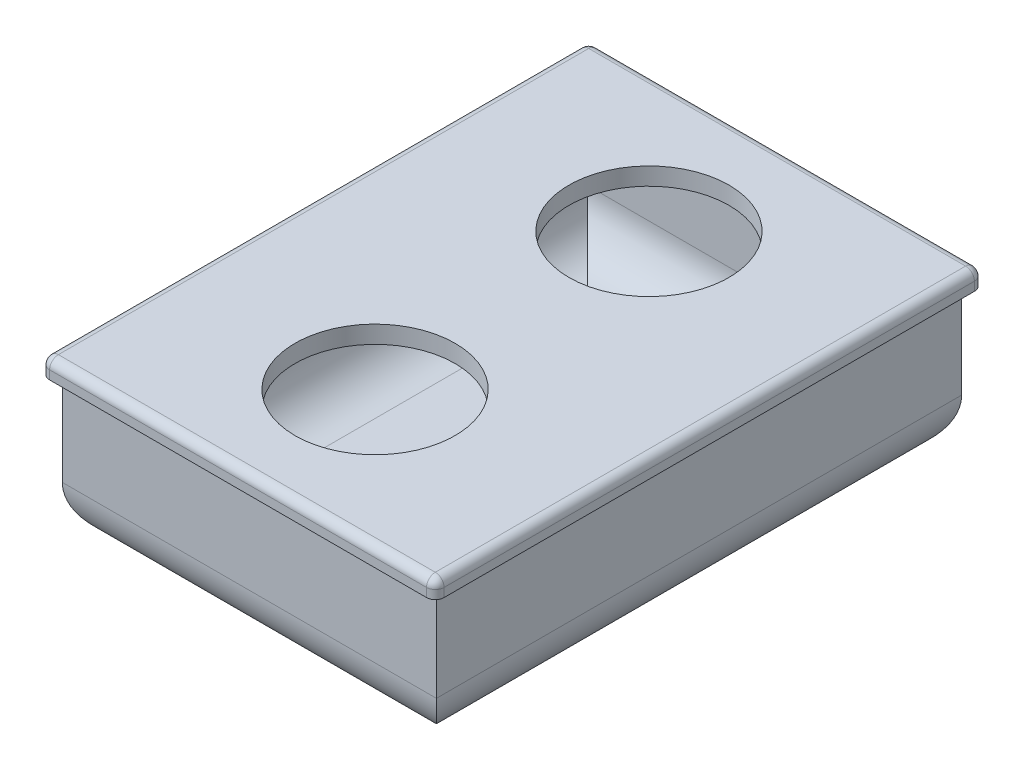
SolidWorks part; units mm, degrees
ref_plane "Front Plane" through (0, 0, 0) normal (0, 0, 1) x (1, 0, 0)
ref_plane "Top Plane" through (0, 0, 0) normal (0, 1, 0) x (1, 0, 0)
ref_plane "Right Plane" through (0, 0, 0) normal (1, 0, 0) x (0, 0, -1)
sketch "Sketch1" plane through (0, 0, 0) normal (0, 1, 0) x (1, 0, 0)
  line L1 (-213.36, -299.593) -> (213.36, -299.593)
  line L2 (-213.36, -299.593) -> (-213.36, 299.593)
  line L3 (-213.36, 299.593) -> (213.36, 299.593)
  line L4 (213.36, -299.593) -> (213.36, 299.593)
  line L5 (-213.36, -299.593) -> (213.36, 299.593) construction
  line L6 (-213.36, 299.593) -> (213.36, -299.593) construction
  point P0 (0, 0)
  dimension "D1" = 426.72
  dimension "D2" = 599.186
extrude "Boss-Extrude1" add sketch "Sketch1" along normal blind 167.64
fillet "Fillet1" radius 60.8 4 edges at (0, 0, -299.593) (-213.36, 0, 0) (0, 0, 299.593) (213.36, 0, 0)
shell "Shell4" thickness 6.35
sketch "Sketch7" plane through (0, 0, 0) normal (0, -1, 0) x (1, 0, 0)
  line L1 (225, 312.5) -> (-225, 312.5)
  line L2 (225, 312.5) -> (225, -312.5)
  line L3 (225, -312.5) -> (-225, -312.5)
  line L4 (-225, 312.5) -> (-225, -312.5)
  line L5 (225, 312.5) -> (-225, -312.5) construction
  line L6 (225, -312.5) -> (-225, 312.5) construction
  point P0 (0, 0)
  dimension "D1" = 450
  dimension "D2" = 625
extrude "Boss-Extrude3" add sketch "Sketch7" against normal blind 20 from surface at -167.64 starting at face at (0, 167.64, 0)
sketch "Sketch8" plane through (0, 0, 0) normal (0, 1, 0) x (1, 0, 0)
  line L0 (0, -312.5) -> (0, 0)
  line L1 (-225, 312.5) -> (225, 312.5)
  line L2 (-225, 312.5) -> (-225, -312.5)
  line L3 (-225, -312.5) -> (225, -312.5)
  line L4 (225, 312.5) -> (225, -312.5)
  line L5 (-225, 312.5) -> (225, -312.5) construction
  line L6 (-225, -312.5) -> (225, 312.5) construction
  line L7 (0, 0) -> (0, -156.25)
  line L8 (0, -156.25) -> (0, 0)
  line L9 (0, 312.5) -> (0, 0)
  line L10 (0, 156.25) -> (0, 0)
  circle A0 centre (0, -156.25) radius 91.2976
  circle A1 centre (0, 156.25) radius 91.2976
  point P0 (0, 0)
  dimension "D1" = 625
  dimension "D2" = 450
extrude "Cut-Extrude4" cut sketch "Sketch8" against normal up to next and the other way through all from surface contours A1 | A0
fillet "Fillet4" radius 10 8 edges at (0, 187.64, 312.5) (225, 187.64, 0) (0, 187.64, -312.5) (-225, 187.64, 0) (-225, 177.64, -312.5) (-225, 177.64, 312.5) (225, 177.64, -312.5) (225, 177.64, 312.5)
